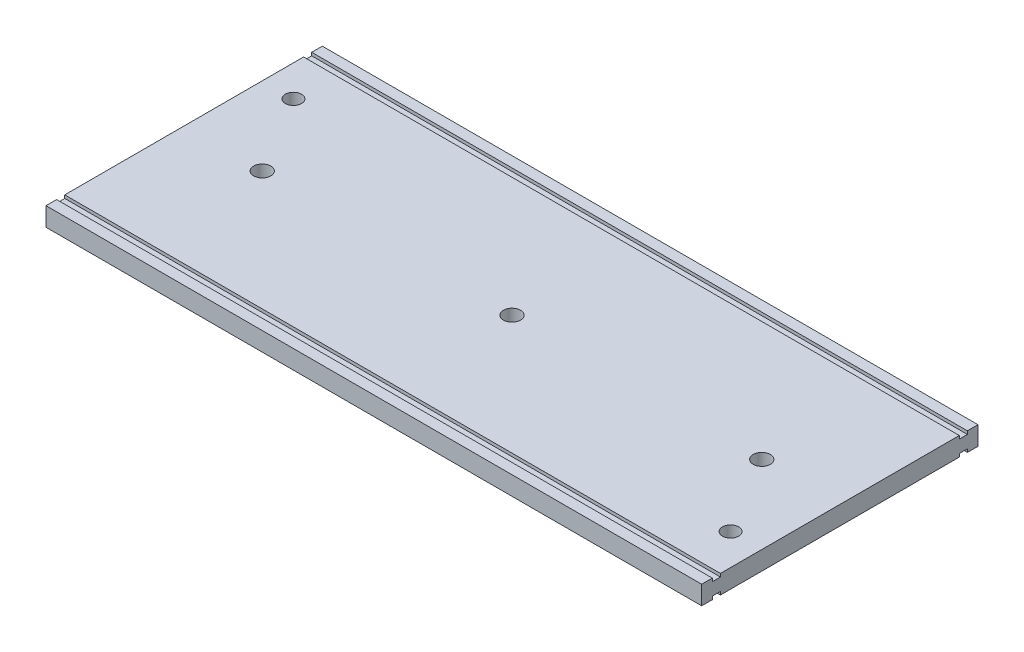
SolidWorks part; units mm, degrees
ref_plane "Front Plane" through (0, 0, 0) normal (0, 0, 1) x (1, 0, 0)
ref_plane "Top Plane" through (0, 0, 0) normal (0, 1, 0) x (1, 0, 0)
ref_plane "Right Plane" through (0, 0, 0) normal (1, 0, 0) x (0, 0, -1)
sketch "Sketch1" plane through (0, 0, 0) normal (0, 1, 0) x (1, 0, 0)
  line L0 (0, -55) -> (0, 55) construction
  line L1 (-105, -44.25) -> (105, -44.25)
  line L2 (-105, -44.25) -> (-105, 44.25)
  line L3 (-105, 44.25) -> (105, 44.25)
  line L4 (105, -44.25) -> (105, 44.25)
  line L5 (-105, -44.25) -> (105, 44.25) construction
  line L6 (-105, 44.25) -> (105, -44.25) construction
  circle A0 centre (80, 0) radius 2.75
  circle A1 centre (0, 0) radius 2.75
  circle A2 centre (-80, 0) radius 2.75
  circle A3 centre (-95, 25) radius 2.6
  circle A4 centre (95, -25) radius 2.6
  point P0 (0, 0)
  dimension "D3" = 5.5
  dimension "D4" = 5.5
  dimension "D6" = 5.2
  dimension "D7" = 5.2
  dimension "D1" = 210
  dimension "D2" = 88.5
  dimension "D5" = 80
  dimension "D8" = 25
  dimension "D9" = 25
  dimension "D10" = 10
  dimension "D11" = 10
extrude "Boss-Extrude1" add sketch "Sketch1" along normal mid plane 6
sketch "Sketch2" plane through (0, 3, 0) normal (0, 1, 0) x (1, 0, 0)
  line L0 (-105, 44.25) -> (-105, -44.25) construction
  line L1 (-105, 40.85) -> (105, 40.85)
  line L2 (-105, 40.85) -> (-105, 38.25)
  line L3 (-105, 38.25) -> (105, 38.25)
  line L4 (105, 40.85) -> (105, 38.25)
  line L5 (105, -44.25) -> (105, 44.25) construction
  line L6 (105, 44.25) -> (-105, 44.25) construction
  line L7 (-55, 0) -> (55, 0) construction
  line L8 (105, -40.85) -> (105, -38.25)
  line L9 (-105, -40.85) -> (-105, -38.25)
  line L10 (-105, -40.85) -> (105, -40.85)
  line L11 (-105, -38.25) -> (105, -38.25)
  dimension "D1" = 2.6
  dimension "D2" = 6
extrude "Cut-Extrude1" cut sketch "Sketch2" against normal blind 1
mirror "Mirror1" about plane through (0, 0, 0) normal (0, 1, 0) of "Cut-Extrude1"
